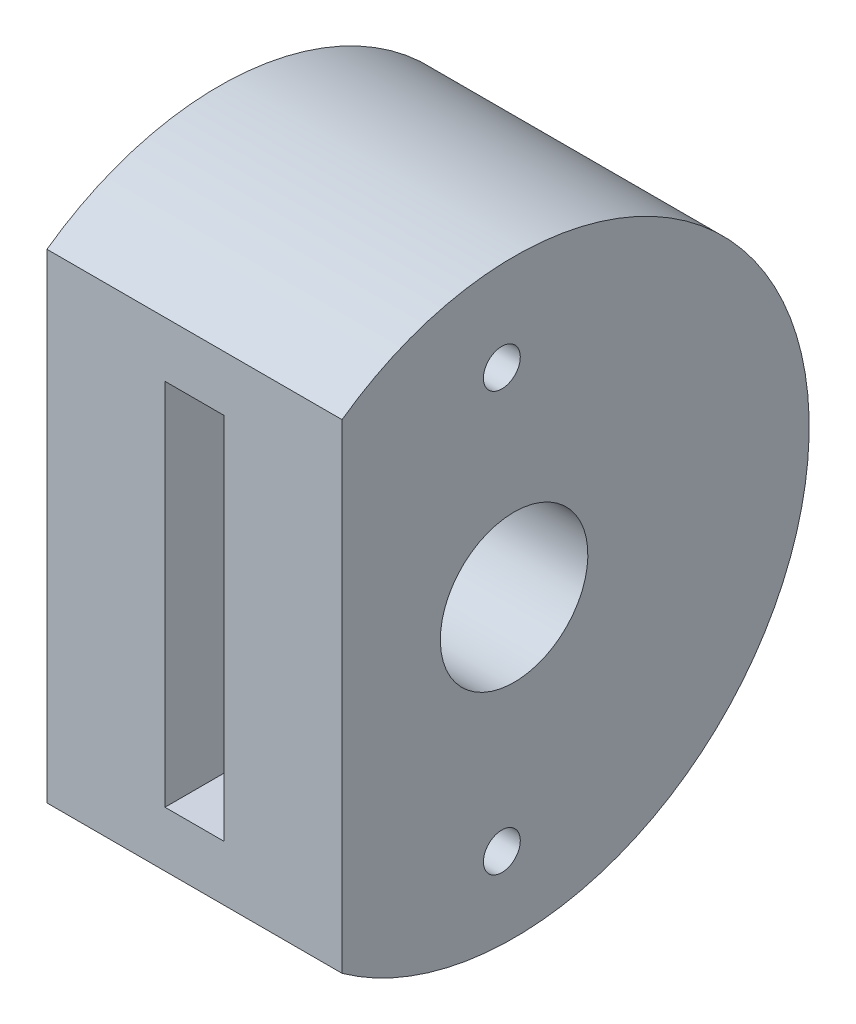
SolidWorks part; units mm, degrees
ref_plane "Plan de face" through (0, 0, 0) normal (0, 0, 1) x (1, 0, 0)
ref_plane "Plan de dessus" through (0, 0, 0) normal (0, 1, 0) x (1, 0, 0)
ref_plane "Plan de droite" through (0, 0, 0) normal (1, 0, 0) x (0, 0, -1)
sketch "Esquisse2" plane through (0, 0, 0) normal (0, 0, 1) x (1, 0, 0)
  line L0 (-55.0457, 21.6016) -> (-55.0457, -49.5484)
  line L1 (24.9543, 27.9003) -> (24.9543, -43.2497)
  line L2 (-55.0457, -49.5484) -> (-55.0457, -83.3084)
  line L3 (-55.0457, 21.6016) -> (-55.0457, 46.6916)
  line L4 (-55.0457, 46.6916) -> (24.9543, 46.6916)
  line L5 (24.9543, 46.6916) -> (24.9543, 27.9003)
  line L6 (-55.0457, -83.3084) -> (24.9543, -83.3084)
  line L7 (24.9543, -83.3084) -> (24.9543, -43.2497)
  dimension "D4" = 25.09
  dimension "D1" = 71.15
  dimension "D2" = 71.15
  dimension "D3" = 80
  dimension "D5" = 33.76
extrude "Boss.-Extru.1" add sketch "Esquisse2" along normal blind 80 from offset 10 offset against normal yes
sketch "Esquisse3" plane through (0, 0, 70) normal (0, 0, 1) x (1, 0, 0)
  line L0 (24.9543, -83.3084) -> (24.9543, 46.6916) construction
  line L1 (-7.0457, -68.3084) -> (-23.0457, -68.3084)
  line L2 (-7.0457, -68.3084) -> (-7.0457, 31.6916)
  line L3 (-7.0457, 31.6916) -> (-23.0457, 31.6916)
  line L4 (-23.0457, -68.3084) -> (-23.0457, 31.6916)
  line L5 (-7.0457, -68.3084) -> (-23.0457, 31.6916) construction
  line L6 (-7.0457, 31.6916) -> (-23.0457, -68.3084) construction
  line L7 (24.9543, 46.6916) -> (-55.0457, 46.6916) construction
  point P0 (-15.0457, -18.3084)
  dimension "D1" = 15
  dimension "D2" = 100
  dimension "D3" = 32
  dimension "D4" = 16
extrude "Enlèv. mat.-Extru.1" cut sketch "Esquisse3" against normal blind 80
ref_plane "Plan3" through (24.9543, 0, 0) normal (1, 0, 0) x (0, 0, -1)
sketch "Esquisse6" plane through (24.9543, 0, 0) normal (1, 0, 0) x (0, 0, -1)
  line L0 (-70, 46.6916) -> (10, 46.6916)
  line L1 (10, 46.6916) -> (10, -83.3084) construction
  line L2 (10, 46.6916) -> (10, -83.3084)
  line L3 (10, -83.3084) -> (-70, -83.3084)
  line L4 (-70, 46.6916) -> (-70, -83.3084) construction
  line L5 (-70, -83.3084) -> (10, -83.3084) construction
  arc A0 (-70, 46.6916) -> (-70, -83.3084) centre (-23.3631, -18.3084) cw
  dimension "D1" = 80
extrude "Boss.-Extru.2" add sketch "Esquisse6" against normal blind 80
sketch "Esquisse8" plane through (24.9543, 0, 0) normal (1, 0, 0) x (0, 0, -1)
  line L0 (-23.3631, -98.3084) -> (-23.3631, 109.3009) construction
  line L1 (56.6369, -18.3084) -> (-107.5435, -18.3084) construction
  arc A0 (-70, -83.3084) -> (-70, 46.6916) centre (-23.3631, -18.3084) ccw construction
  circle A1 centre (-23.3631, -18.3084) radius 20
  dimension "D1" = 40
fillet "Congé1" radius 11 2 edges at (-15.0457, 31.6916, -10) (-15.0457, -68.3084, -10)
extrude "Enlèv. mat.-Extru.2" cut sketch "Esquisse8" against normal up to surface (80 mm away) up to face at (-55.0457, -18.3084, 6.6816)
sketch "Esquisse9" plane through (-55.0457, 0, 0) normal (-1, 0, 0) x (0, 0, 1)
  circle A0 centre (26.6811, 37.258) radius 5
  circle A1 centre (26.6811, -76.2999) radius 5
  dimension "D1" = 10
  dimension "D2" = 10
extrude "Enlèv. mat.-Extru.3" cut sketch "Esquisse9" against normal blind 80
scale "Echelle1" scale about centroid uniform scaling yes scale factor 0.25
